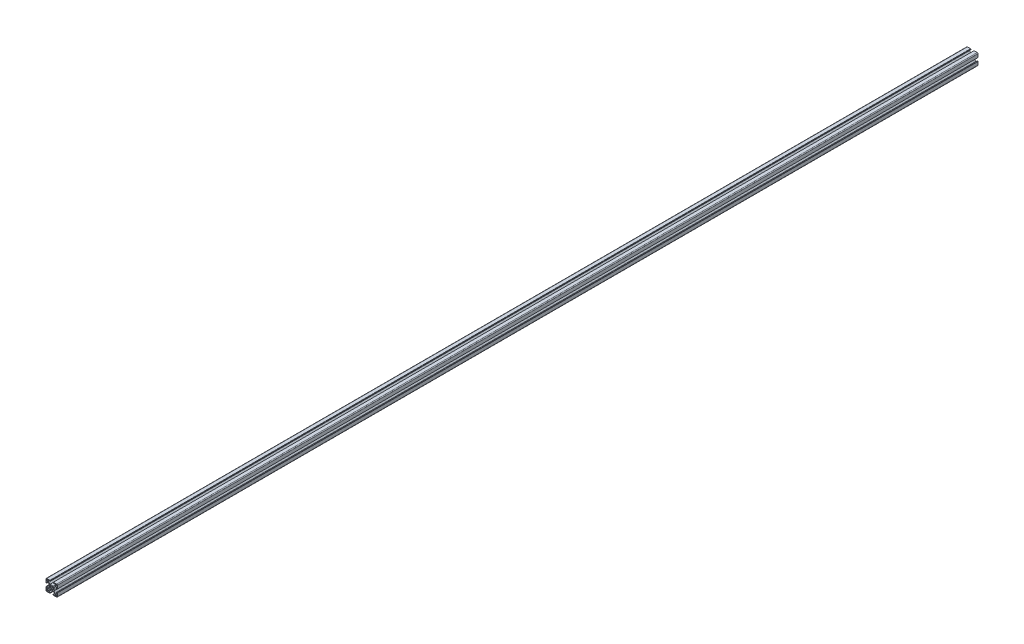
SolidWorks part; units mm, degrees
ref_plane "Front Plane" through (0, 0, 0) normal (0, 0, 1) x (1, 0, 0)
ref_plane "Top Plane" through (0, 0, 0) normal (0, 1, 0) x (1, 0, 0)
ref_plane "Right Plane" through (0, 0, 0) normal (1, 0, 0) x (0, 0, -1)
sketch "Sketch1" plane through (0, 0, 0) normal (0, 0, 1) x (1, 0, 0)
  line L0 (-15, 0) -> (15, 0) construction
  line L1 (0, -15) -> (0, 15) construction
  line L2 (-4.5, 15) -> (4.5, 15) construction
  line L3 (-4, -15) -> (4, -15) construction
  line L4 (-4.5, 15) -> (-4.5, 14.5)
  line L5 (-4.5, 14.5) -> (-4, 14.5)
  line L6 (-4, 14.5) -> (-4, 12.71)
  line L7 (-4, 12.71) -> (-8.2, 12.71)
  line L8 (-8.2, 12.71) -> (-8.2, 9.9961)
  line L9 (-8.2, 9.9961) -> (-4.2039, 6)
  line L10 (-4.2039, 6) -> (0, 6)
  line L11 (0, 0) -> (-15, 15) construction
  line L12 (-4.5, 15) -> (-12.968, 15)
  line L13 (-4.4937, 3.1431) -> (-3.1431, 4.4937)
  line L14 (-13.47, 9.79) -> (-9.79, 9.79)
  line L15 (-13.47, 9.79) -> (-13.47, 13.47)
  line L16 (-13.47, 13.47) -> (-9.79, 13.47)
  line L17 (-9.79, 9.79) -> (-9.79, 13.47)
  line L18 (-13.47, 9.79) -> (-9.79, 13.47) construction
  line L19 (-13.47, 13.47) -> (-9.79, 9.79) construction
  line L20 (-3.1431, 4.4937) -> (-1.7057, 3.0563)
  line L21 (-4.4937, 3.1431) -> (-3.0563, 1.7057)
  line L22 (-6, 4.2039) -> (-6, 0)
  line L23 (-9.9961, 8.2) -> (-6, 4.2039)
  line L24 (-15, 4.5) -> (-15, 12.968)
  line L25 (-12.71, 8.2) -> (-9.9961, 8.2)
  line L26 (-12.71, 4) -> (-12.71, 8.2)
  line L27 (-14.5, 4) -> (-12.71, 4)
  line L28 (-14.5, 4.5) -> (-14.5, 4)
  line L29 (-15, 4.5) -> (-14.5, 4.5)
  circle A0 centre (0, 0) radius 3.5
  arc A1 (-12.968, 15) -> (-15, 12.968) centre (-12.968, 12.968) ccw
  point P4 (0, 0)
  point P8 (0, 0)
  point P13 (0, 15)
  point P15 (0, -15)
  point P16 (0, 6)
  point P23 (-11.63, 11.63)
  point P26 (0, 6)
  point P33 (-3.8184, 3.8184)
  dimension "Center Hole Diameter" = 7
  dimension "D11" = 2.032
  dimension "Rail Height" = 30
  dimension "Rail Width" = 30
  dimension "T-Slot Width" = 8
  dimension "T-Slot Depth" = 9
  dimension "D1" = 9
  dimension "D2" = 45
  dimension "D3" = 8
  dimension "D4" = 2.29
  dimension "D5" = 16.4
  dimension "D7" = 2.54
  dimension "D6" = 3.37
  dimension "D8" = 3.68
  dimension "D9" = 5.4
  dimension "D10" = 1.91
sketch "Sketch2" plane through (0, 0, 0) normal (1, 0, 0) x (0, 0, -1)
  line L0 (-1219.2, 0) -> (1219.2, 0) construction
  line L2 (0, -15) -> (0, 15) construction
  line L3 (0, -15) -> (0, 15) construction
  line L4 (-1219.2, -15) -> (-1219.2, 15) construction
  line L5 (1219.2, -15) -> (1219.2, 15) construction
  point P0 (-1181.7, 0)
  point P3 (0, 0)
  point P4 (1181.7, 0)
  point P12 (-1219.2, 0)
  point P14 (1219.2, 0)
  dimension "Length" = 2438.4
  dimension "D1" = 37.5
sketch "Sketch3" plane through (0, 0, 0) normal (0, 0, 1) x (1, 0, 0)
  line L0 (-3.1431, 4.4937) -> (-1.7057, 3.0563) construction
  line L1 (-4.4937, 3.1431) -> (-3.1431, 4.4937) construction
  line L2 (-4.4937, 3.1431) -> (-3.0563, 1.7057) construction
  line L4 (-13.47, 9.79) -> (-9.79, 9.79)
  line L5 (-9.79, 9.79) -> (-9.79, 13.47)
  line L6 (-9.79, 13.47) -> (-13.47, 13.47)
  line L7 (-13.47, 13.47) -> (-13.47, 9.79)
  line L8 (-13.47, 9.79) -> (-9.79, 9.79)
  line L9 (-9.79, 9.79) -> (-9.79, 13.47)
  line L10 (-9.79, 13.47) -> (-13.47, 13.47)
  line L11 (-13.47, 13.47) -> (-13.47, 9.79)
  line L12 (-4.2039, 6) -> (0, 6) construction
  line L13 (-8.2, 9.9961) -> (-4.2039, 6) construction
  line L14 (-8.2, 12.71) -> (-8.2, 9.9961) construction
  line L15 (-4, 12.71) -> (-8.2, 12.71) construction
  line L16 (-4, 14.5) -> (-4, 12.71) construction
  line L17 (-4.5, 14.5) -> (-4, 14.5) construction
  line L18 (-4.5, 15) -> (-4.5, 14.5) construction
  line L19 (-4.5, 15) -> (-12.968, 15) construction
  line L20 (-15, 4.5) -> (-15, 12.968) construction
  line L21 (-15, 4.5) -> (-14.5, 4.5) construction
  line L22 (-14.5, 4.5) -> (-14.5, 4) construction
  line L23 (-14.5, 4) -> (-12.71, 4) construction
  line L24 (-12.71, 4) -> (-12.71, 8.2) construction
  line L25 (-12.71, 8.2) -> (-9.9961, 8.2) construction
  line L26 (-9.9961, 8.2) -> (-6, 4.2039) construction
  line L27 (-6, 4.2039) -> (-6, 0) construction
  line L28 (-3.1431, 4.4937) -> (-1.7057, 3.0563)
  line L29 (-4.4937, 3.1431) -> (-3.1431, 4.4937)
  line L30 (-4.4937, 3.1431) -> (-3.0563, 1.7057)
  line L32 (-4.2039, 6) -> (0, 6)
  line L33 (-8.2, 9.9961) -> (-4.2039, 6)
  line L34 (-8.2, 12.71) -> (-8.2, 9.9961)
  line L35 (-4, 12.71) -> (-8.2, 12.71)
  line L36 (-4, 14.5) -> (-4, 12.71)
  line L37 (-4.5, 14.5) -> (-4, 14.5)
  line L38 (-4.5, 15) -> (-4.5, 14.5)
  line L39 (-4.5, 15) -> (-12.968, 15)
  line L40 (-15, 4.5) -> (-15, 12.968)
  line L41 (-15, 4.5) -> (-14.5, 4.5)
  line L42 (-14.5, 4.5) -> (-14.5, 4)
  line L43 (-14.5, 4) -> (-12.71, 4)
  line L44 (-12.71, 4) -> (-12.71, 8.2)
  line L45 (-12.71, 8.2) -> (-9.9961, 8.2)
  line L46 (-9.9961, 8.2) -> (-6, 4.2039)
  line L47 (-6, 4.2039) -> (-6, 0)
  line L48 (9.79, 13.47) -> (9.79, 9.79)
  line L49 (9.79, 9.79) -> (13.47, 9.79)
  line L50 (13.47, 9.79) -> (13.47, 13.47)
  line L51 (13.47, 13.47) -> (9.79, 13.47)
  line L52 (4.4937, 3.1431) -> (3.0563, 1.7057)
  line L53 (3.1431, 4.4937) -> (4.4937, 3.1431)
  line L54 (3.1431, 4.4937) -> (1.7057, 3.0563)
  line L55 (6, 4.2039) -> (6, 0)
  line L56 (9.9961, 8.2) -> (6, 4.2039)
  line L57 (12.71, 8.2) -> (9.9961, 8.2)
  line L58 (12.71, 4) -> (12.71, 8.2)
  line L59 (14.5, 4) -> (12.71, 4)
  line L60 (14.5, 4.5) -> (14.5, 4)
  line L61 (15, 4.5) -> (14.5, 4.5)
  line L62 (15, 4.5) -> (15, 12.968)
  line L63 (4.5, 15) -> (12.968, 15)
  line L64 (4.5, 15) -> (4.5, 14.5)
  line L65 (4.5, 14.5) -> (4, 14.5)
  line L66 (4, 14.5) -> (4, 12.71)
  line L67 (4, 12.71) -> (8.2, 12.71)
  line L68 (8.2, 12.71) -> (8.2, 9.9961)
  line L69 (8.2, 9.9961) -> (4.2039, 6)
  line L70 (4.2039, 6) -> (0, 6)
  line L71 (13.47, -9.79) -> (9.79, -9.79)
  line L72 (9.79, -9.79) -> (9.79, -13.47)
  line L73 (9.79, -13.47) -> (13.47, -13.47)
  line L74 (13.47, -13.47) -> (13.47, -9.79)
  line L75 (3.1431, -4.4937) -> (1.7057, -3.0563)
  line L76 (4.4937, -3.1431) -> (3.1431, -4.4937)
  line L77 (4.4937, -3.1431) -> (3.0563, -1.7057)
  line L78 (4.2039, -6) -> (0, -6)
  line L79 (8.2, -9.9961) -> (4.2039, -6)
  line L80 (8.2, -12.71) -> (8.2, -9.9961)
  line L81 (4, -12.71) -> (8.2, -12.71)
  line L82 (4, -14.5) -> (4, -12.71)
  line L83 (4.5, -14.5) -> (4, -14.5)
  line L84 (4.5, -15) -> (4.5, -14.5)
  line L85 (4.5, -15) -> (12.968, -15)
  line L86 (15, -4.5) -> (15, -12.968)
  line L87 (15, -4.5) -> (14.5, -4.5)
  line L88 (14.5, -4.5) -> (14.5, -4)
  line L89 (14.5, -4) -> (12.71, -4)
  line L90 (12.71, -4) -> (12.71, -8.2)
  line L91 (12.71, -8.2) -> (9.9961, -8.2)
  line L92 (9.9961, -8.2) -> (6, -4.2039)
  line L93 (6, -4.2039) -> (6, 0)
  line L94 (-9.79, -13.47) -> (-9.79, -9.79)
  line L95 (-9.79, -9.79) -> (-13.47, -9.79)
  line L96 (-13.47, -9.79) -> (-13.47, -13.47)
  line L97 (-13.47, -13.47) -> (-9.79, -13.47)
  line L98 (-4.4937, -3.1431) -> (-3.0563, -1.7057)
  line L99 (-3.1431, -4.4937) -> (-4.4937, -3.1431)
  line L100 (-3.1431, -4.4937) -> (-1.7057, -3.0563)
  line L101 (-6, -4.2039) -> (-6, 0)
  line L102 (-9.9961, -8.2) -> (-6, -4.2039)
  line L103 (-12.71, -8.2) -> (-9.9961, -8.2)
  line L104 (-12.71, -4) -> (-12.71, -8.2)
  line L105 (-14.5, -4) -> (-12.71, -4)
  line L106 (-14.5, -4.5) -> (-14.5, -4)
  line L107 (-15, -4.5) -> (-14.5, -4.5)
  line L108 (-15, -4.5) -> (-15, -12.968)
  line L109 (-4.5, -15) -> (-12.968, -15)
  line L110 (-4.5, -15) -> (-4.5, -14.5)
  line L111 (-4.5, -14.5) -> (-4, -14.5)
  line L112 (-4, -14.5) -> (-4, -12.71)
  line L113 (-4, -12.71) -> (-8.2, -12.71)
  line L114 (-8.2, -12.71) -> (-8.2, -9.9961)
  line L115 (-8.2, -9.9961) -> (-4.2039, -6)
  line L116 (-4.2039, -6) -> (0, -6)
  arc A0 (-12.968, 15) -> (-15, 12.968) centre (-12.968, 12.968) ccw construction
  circle A1 centre (0, 0) radius 3.5
  arc A2 (-3.0563, 1.7057) -> (-3.0563, -1.7057) centre (0, 0) ccw
  arc A3 (-12.968, 15) -> (-15, 12.968) centre (-12.968, 12.968) ccw
  arc A4 (15, 12.968) -> (12.968, 15) centre (12.968, 12.968) ccw
  arc A5 (12.968, -15) -> (15, -12.968) centre (12.968, -12.968) ccw
  arc A6 (-15, -12.968) -> (-12.968, -15) centre (-12.968, -12.968) ccw
  arc A7 (1.7057, 3.0563) -> (-1.7057, 3.0563) centre (0, 0) ccw
  arc A8 (3.0563, -1.7057) -> (3.0563, 1.7057) centre (0, 0) ccw
  arc A9 (-1.7057, -3.0563) -> (1.7057, -3.0563) centre (0, 0) ccw
  point P116 (0, 0)
  dimension "D1" = 0
  dimension "D2" = 0
  dimension "D3" = 4
extrude "Boss-Extrude1" add sketch "Sketch3" along normal mid plane 2438.4
equation "\"D1@Sketch2\" = \"Rail Height@Sketch1\" * 1.25"
equation "\"D1@Sketch1\"=\"T-Slot Width@Sketch1\"+1mm"
equation "\"D3@Sketch1\"=\"T-Slot Width@Sketch1\""
equation "\"D1@Boss-Extrude1\"=\"Length@Sketch2\""
